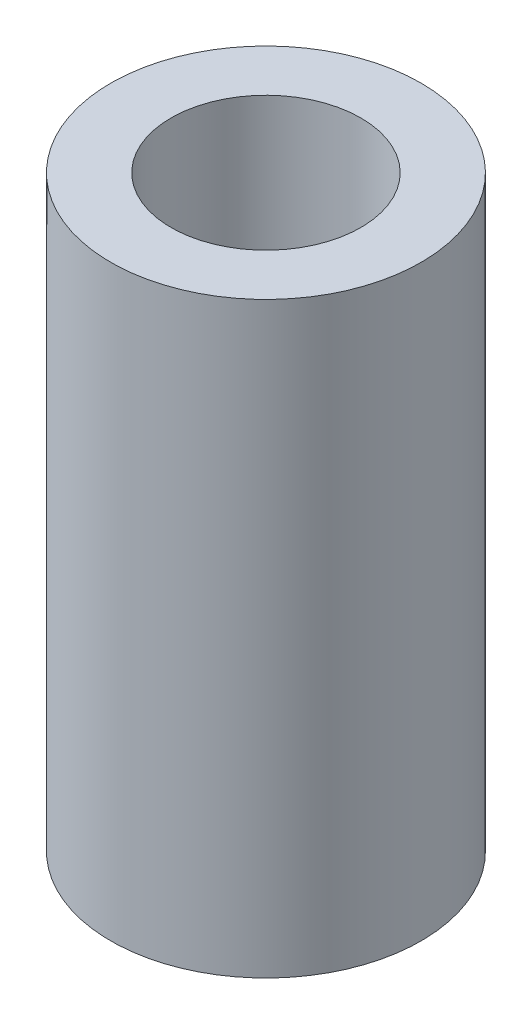
SolidWorks part; units mm, degrees
ref_plane "Ebene vorne" through (0, 0, 0) normal (0, 0, 1) x (1, 0, 0)
ref_plane "Ebene oben" through (0, 0, 0) normal (0, 1, 0) x (1, 0, 0)
ref_plane "Ebene rechts" through (0, 0, 0) normal (1, 0, 0) x (0, 0, -1)
sketch "Skizze1" plane through (0, 0, 0) normal (0, 0, 1) x (1, 0, 0)
  line L0 (-4.35, 0) -> (-4.35, 9.25)
  line L1 (-4.35, 9.25) -> (0, 9.25)
  line L2 (0, 9.25) -> (0, 10.25)
  line L3 (0, 10.25) -> (-3.15, 10.25)
  line L4 (-3.15, 10.25) -> (-3.15, 19.5)
  line L5 (-3.15, 19.5) -> (-5.15, 19.5)
  line L6 (-5.15, 19.5) -> (-5.15, 0)
  line L7 (-5.15, 0) -> (-4.35, 0)
  line L8 (0, 0) -> (0, 19.5) construction
  dimension "D1" = 6.3
  dimension "D2" = 8.7
  dimension "D3" = 0.8
  dimension "D4" = 1
  dimension "D5" = 19.5
revolve "Rotation1" add sketch "Skizze1" angle 360 about L8
